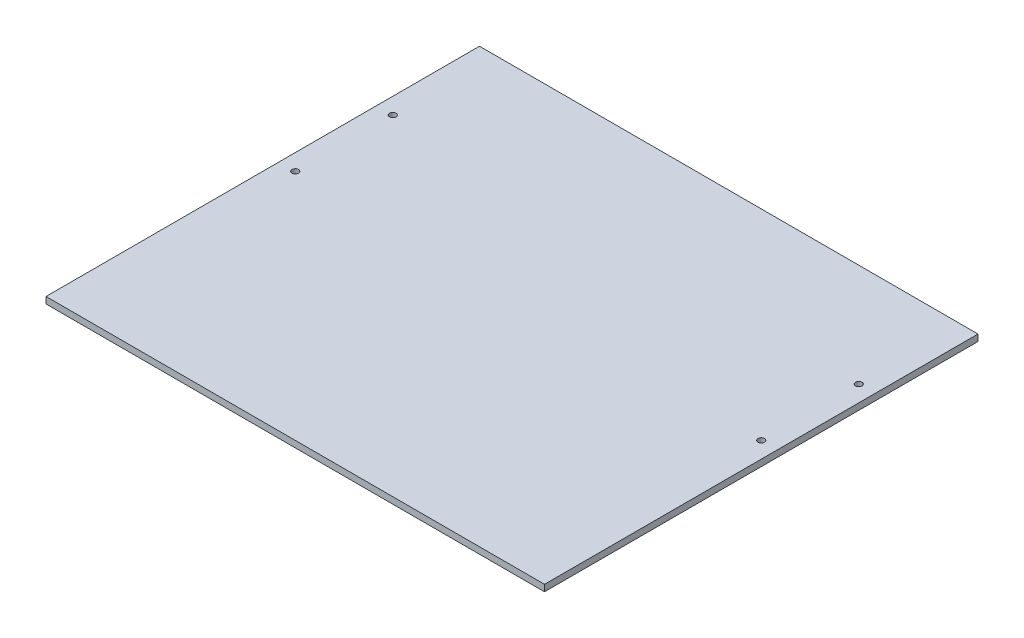
SolidWorks part; units mm, degrees
material "1023 Chapa de aço carbono (SS)"
ref_plane "Plano frontal" through (0, 0, 0) normal (0, 0, 1) x (1, 0, 0)
ref_plane "Plano superior" through (0, 0, 0) normal (0, 1, 0) x (1, 0, 0)
ref_plane "Plano direito" through (0, 0, 0) normal (1, 0, 0) x (0, 0, -1)
sketch "Esboço1" plane through (0, 0, 0) normal (0, 1, 0) x (1, 0, 0)
  line L0 (-107.5, 7.5) -> (-107.5, 52.5) construction
  line L1 (-115, -100) -> (115, -100)
  line L2 (-115, -100) -> (-115, 100)
  line L3 (-115, 100) -> (115, 100)
  line L4 (115, -100) -> (115, 100)
  line L5 (-115, -100) -> (115, 100) construction
  line L6 (-115, 100) -> (115, -100) construction
  line L7 (0, 100) -> (0, -100) construction
  line L8 (107.5, 7.5) -> (107.5, 52.5) construction
  circle A0 centre (-107.5, 52.5) radius 1.5
  circle A1 centre (-107.5, 7.5) radius 1.5
  circle A2 centre (107.5, 7.5) radius 1.5
  circle A3 centre (107.5, 52.5) radius 1.5
  point P0 (0, 0)
  point P20 (-107.5, 30)
  dimension "D4" = 3
  dimension "D1" = 200
  dimension "D2" = 230
  dimension "D3" = 45
  dimension "D5" = 7.5
  dimension "D6" = 70
extrude "Ressalto-extrusão1" add sketch "Esboço1" along normal blind 3
